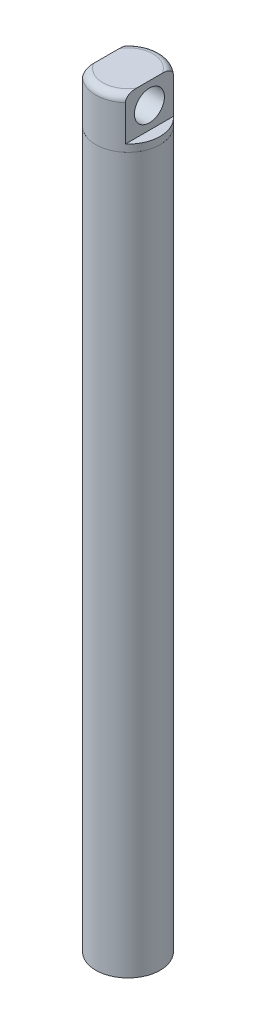
SolidWorks part; units mm, degrees
ref_plane "Спереди" through (0, 0, 0) normal (0, 0, 1) x (1, 0, 0)
ref_plane "Сверху" through (0, 0, 0) normal (0, 1, 0) x (1, 0, 0)
ref_plane "Справа" through (0, 0, 0) normal (1, 0, 0) x (0, 0, -1)
sketch "Эскиз1" plane through (0, 0, 0) normal (0, 1, 0) x (1, 0, 0)
  circle A0 centre (0, 0) radius 4.5
extrude "Вытянуть1" add sketch "Эскиз1" along normal blind 100
sketch "Эскиз2" plane through (0, 100, 0) normal (0, 1, 0) x (1, 0, 0)
  circle A0 centre (0, 0) radius 4.5
extrude "Вытянуть2" add sketch "Эскиз2" along normal blind 7 separate body
fillet "Скругление1" radius 1 1 edges at (0, 107, 4.5)
sketch "Эскиз3" plane through (0, 0, 0) normal (0, 0, 1) x (1, 0, 0)
  line L0 (0, 107) -> (0, 115.5292) construction
  line L2 (3.5, 107) -> (-3.5, 107) construction
  line L3 (-5.3764, 110.201) -> (-3, 110.201)
  line L4 (-5.3764, 110.201) -> (-5.3764, 101)
  line L5 (-5.3764, 101) -> (-3, 101)
  line L6 (-3, 110.201) -> (-3, 101)
  line L7 (5.3764, 101) -> (3, 101)
  line L8 (3, 110.201) -> (3, 101)
  line L9 (5.3764, 110.201) -> (3, 110.201)
  line L10 (5.3764, 110.201) -> (5.3764, 101)
  dimension "D1" = 6
  dimension "D2" = 3
  dimension "D3" = 6
extrude "Вытянуть3" cut sketch "Эскиз3" against normal mid plane 27
sketch "Эскиз4" plane through (3, 0, 0) normal (1, 0, 0) x (0, 0, -1)
  line L0 (3.8555, 100) -> (16.685, 100) construction
  circle A0 centre (0, 104) radius 2.1
  dimension "D1" = 4
extrude "Вытянуть4" cut sketch "Эскиз4" against normal through all
